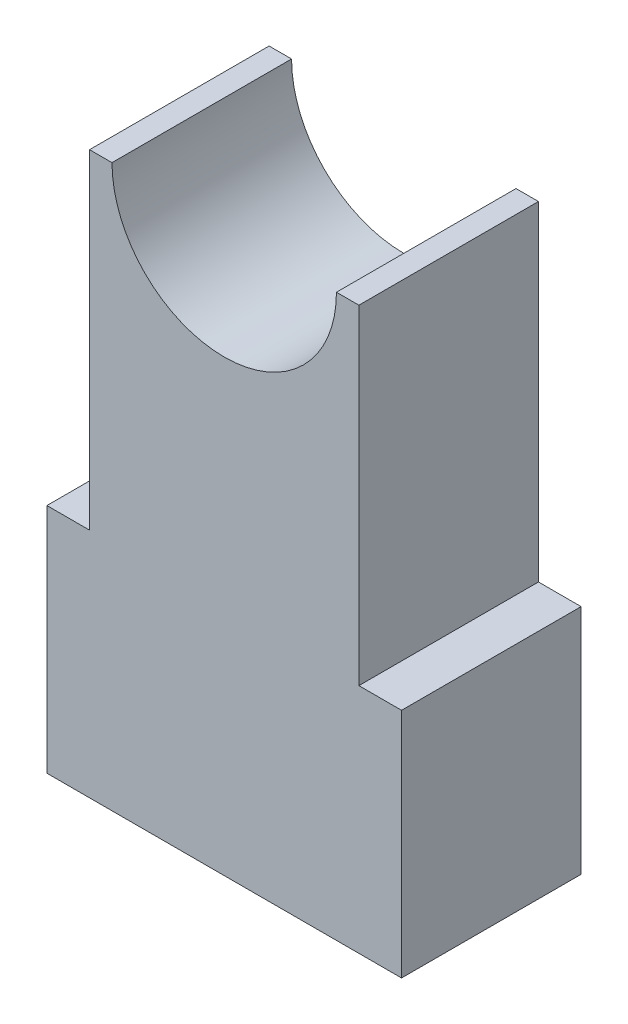
SolidWorks part; units mm, degrees
ref_plane "Plan de face" through (0, 0, 0) normal (0, 0, 1) x (1, 0, 0)
ref_plane "Plan de dessus" through (0, 0, 0) normal (0, 1, 0) x (1, 0, 0)
ref_plane "Plan de droite" through (0, 0, 0) normal (1, 0, 0) x (0, 0, -1)
sketch "Esquisse1" plane through (0, 0, 0) normal (0, 1, 0) x (1, 0, 0)
  line L0 (0, 0) -> (0, 8)
  line L1 (0, 8) -> (15.8, 8)
  line L2 (15.8, 8) -> (15.8, 0)
  line L3 (15.8, 0) -> (0, 0)
  dimension "D1" = 8
  dimension "D2" = 15.8
extrude "Boss.-Extru.1" add sketch "Esquisse1" along normal blind 25.01
sketch "Esquisse2" plane through (0, 0, 0) normal (0, -1, 0) x (1, 0, 0)
  line L0 (0, -4) -> (15.8, -4) construction
  line L1 (0, -8) -> (0, 0) construction
  line L2 (15.8, 0) -> (15.8, -8) construction
  circle A0 centre (3.95, -4) radius 2.4
  circle A1 centre (11.85, -4) radius 2.4
  dimension "D1" = 4.8
  dimension "D2" = 7.9
  dimension "D3" = 3.95
extrude "Enlèv. mat.-Extru.1" cut sketch "Esquisse2" against normal blind 1.7
sketch "Esquisse3" plane through (0, 25.01, 0) normal (0, 1, 0) x (1, 0, 0)
  line L0 (0, 8) -> (1.9, 8)
  line L1 (15.8, 8) -> (0, 8) construction
  line L2 (1.9, 8) -> (1.9, 0)
  line L3 (0, 0) -> (15.8, 0) construction
  line L4 (1.9, 0) -> (0, 0)
  line L5 (0, 0) -> (0, 8)
  line L6 (7.9, 8) -> (7.9, 0) construction
  line L7 (15.8, 0) -> (15.8, 8)
  line L8 (13.9, 0) -> (15.8, 0)
  line L9 (13.9, 8) -> (13.9, 0)
  line L10 (15.8, 8) -> (13.9, 8)
  dimension "D1" = 1.9
extrude "Enlèv. mat.-Extru.2" cut sketch "Esquisse3" against normal blind 14.68
fillet "Congé1" radius 0.2 2 edges at (11.85, 1.7, -6.4) (3.95, 1.7, -6.4)
sketch "Esquisse5" plane through (0, 0, 0) normal (0, 0, 1) x (1, 0, 0)
  line L1 (1.9, 25.01) -> (13.9, 25.01) construction
  arc A0 (2.9, 25.01) -> (12.9, 25.01) centre (7.9, 25.01) ccw
extrude "Enlèv. mat.-Extru.4" cut sketch "Esquisse5" against normal through all and the other way through all
